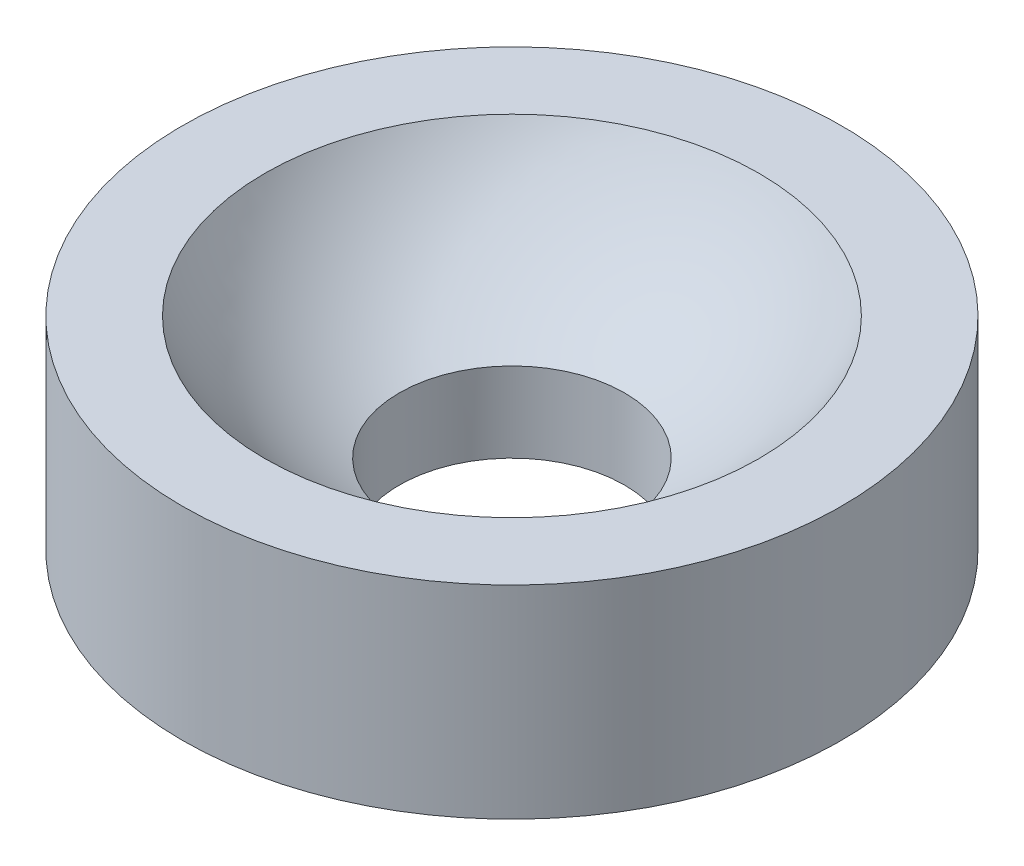
SolidWorks part; units mm, degrees
material "1023 Carbon Steel Sheet (SS)"
ref_plane "Front Plane" through (0, 0, 0) normal (0, 0, 1) x (1, 0, 0)
ref_plane "Top Plane" through (0, 0, 0) normal (0, 1, 0) x (1, 0, 0)
ref_plane "Right Plane" through (0, 0, 0) normal (1, 0, 0) x (0, 0, -1)
sketch "Sketch1" plane through (0, 0, 0) normal (0, 1, 0) x (1, 0, 0)
  circle A0 centre (0, 0) radius 5.85
  dimension "D1" = 11.7
extrude "Boss-Extrude1" add sketch "Sketch1" along normal blind 3.6
sketch "Sketch2" plane through (0, 0, 0) normal (0, 0, 1) x (1, 0, 0)
  line L0 (0, 1) -> (0, 11)
  arc A0 (0, 11) -> (0, 1) centre (0, 6) cw
  dimension "D1" = 10
  dimension "D2" = 1
revolve "Cut-Revolve1" cut sketch "Sketch2" angle 360 about L0
sketch "Sketch3" plane through (0, 0, 0) normal (0, -1, 0) x (1, 0, 0)
  circle A0 centre (0, 0) radius 2
  dimension "D1" = 4
extrude "Cut-Extrude1" cut sketch "Sketch3" against normal blind 4
